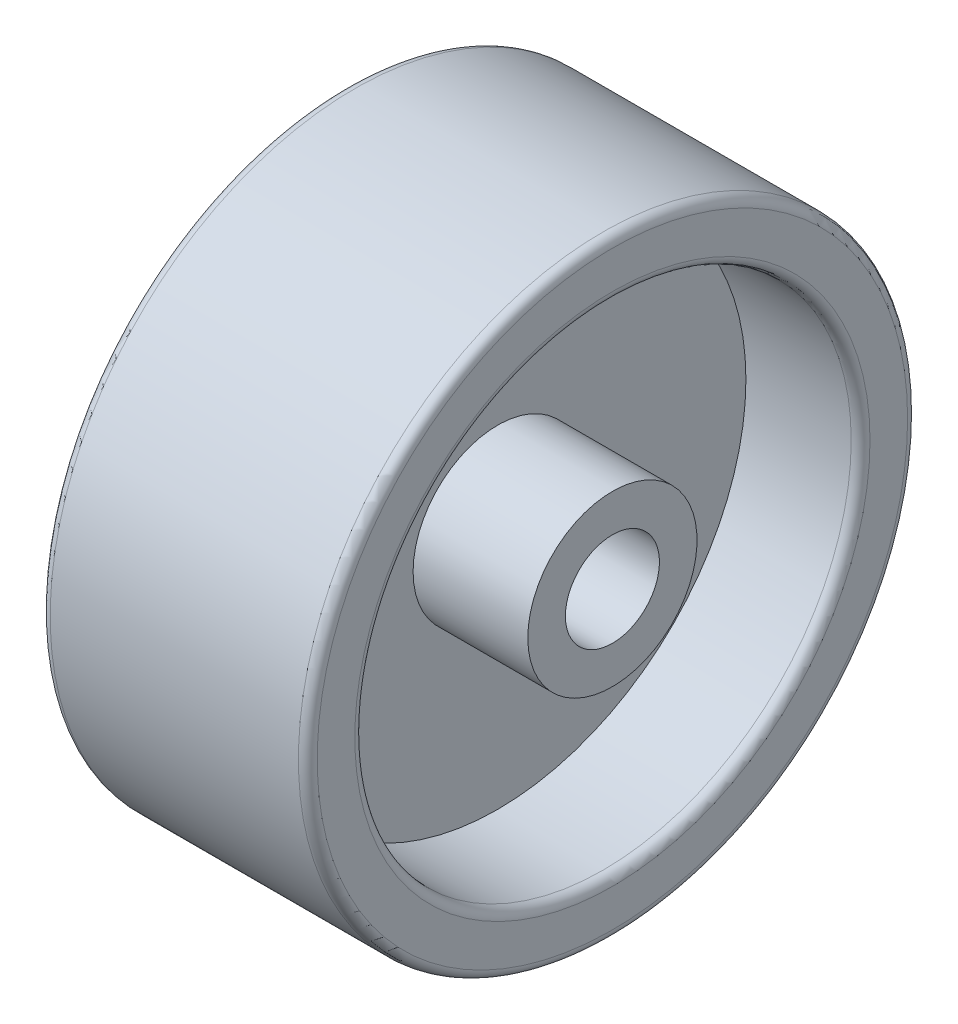
SolidWorks part; units mm, degrees
ref_plane "Front Plane" through (0, 0, 0) normal (0, 0, 1) x (1, 0, 0)
ref_plane "Top Plane" through (0, 0, 0) normal (0, 1, 0) x (1, 0, 0)
ref_plane "Right Plane" through (0, 0, 0) normal (1, 0, 0) x (0, 0, -1)
sketch "Sketch1" plane through (0, 0, 0) normal (1, 0, 0) x (0, 0, -1)
  circle A0 centre (0, 0) radius 16.2
extrude "Boss-Extrude1" add sketch "Sketch1" along normal mid plane 14.2
sketch "Sketch6" plane through (-7.1, 0, 0) normal (-1, 0, 0) x (0, 0, 1)
  circle A0 centre (0, 0) radius 13.2
  circle A1 centre (0, 0) radius 4.5
extrude "Cut-Extrude2" cut sketch "Sketch6" against normal blind 6.1 contours A0
ref_plane "Plane1" through (0, 0, 0) normal (1, 0, 0) x (0, 0, -1)
mirror "Mirror1" about plane through (0, 0, 0) normal (1, 0, 0) of "Cut-Extrude2"
fillet "Fillet2" radius 0.5 1 edges at (-7.1, 0, -16.2)
fillet "Fillet3" radius 0.5 1 edges at (-7.1, 0, 13.2)
fillet "Fillet4" radius 0.5 1 edges at (7.1, 0, 13.2)
fillet "Fillet5" radius 0.5 1 edges at (7.1, 0, -16.2)
sketch "Sketch7" plane through (-7.1, 0, 0) normal (-1, 0, 0) x (0, 0, 1)
  circle A0 centre (0, 0) radius 2.5
extrude "Cut-Extrude3" cut sketch "Sketch7" against normal through all
